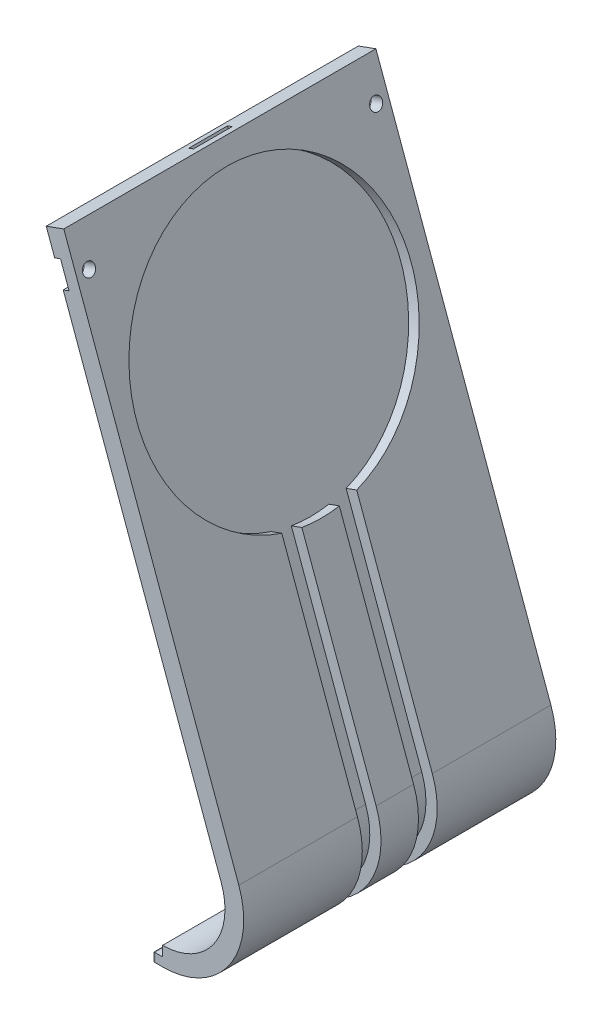
SolidWorks part; units mm, degrees
material "PLA"
ref_plane "前视基准面" through (0, 0, 0) normal (0, 0, 1) x (1, 0, 0)
ref_plane "上视基准面" through (0, 0, 0) normal (0, 1, 0) x (1, 0, 0)
ref_plane "右视基准面" through (0, 0, 0) normal (1, 0, 0) x (0, 0, -1)
other "Configuration Table"
sketch "草图2" plane through (0, 0, 0) normal (0, 0, 1) x (1, 0, 0)
  line L0 (38.2711, 18.4699) -> (5.8755, 107.4762) construction
  line L5 (38.2711, 18.4699) -> (10.2328, 95.5045)
  line L7 (38.2711, 18.4699) -> (8.6116, 99.9586) construction
  line L9 (9.2093, 101.2404) -> (11.5585, 102.0954) construction
  line L10 (28.8742, 5.0497) -> (28.8742, 4.0497) construction
  arc A0 (28.8742, 5.0497) -> (38.2711, 18.4699) centre (28.8742, 15.0497) ccw
  arc A1 (28.8742, 5.0497) -> (38.2711, 18.4699) centre (28.8742, 15.0497) ccw construction
  point P0 (9.5403, 97.4071)
  dimension "D2" = 10
  dimension "D1" = 5.74
extrude "整体拉伸-薄壁1" add sketch "草图2" along normal mid plane 50 thin
sketch "草图4" plane through (42.5494, 15.4867, 0) normal (0.9397, 0.342, 0) x (0, 0, -1)
  line L0 (-25, 86.245) -> (25, 86.245) construction
  circle A0 centre (0, 60.845) radius 22
  dimension "D1" = 44
  dimension "D2" = 25.4
extrude "中间圆切除-拉伸1" cut sketch "草图4" against normal blind 1.8
sketch "草图3" plane through (0, 0, 0) normal (0, 0, 1) x (1, 0, 0)
  line L0 (41.0902, 19.4959) -> (13.0519, 96.5306) construction
  line L1 (41.0902, 19.4959) -> (13.0519, 96.5306) construction
  line L2 (28.8742, 2.0497) -> (28.8742, 5.0497) construction
  line L5 (39.3988, 18.8803) -> (27.5722, 51.3735)
  line L6 (39.3988, 18.8803) -> (11.3604, 95.9149) construction
  line L7 (28.8742, 3.8497) -> (28.8742, 3.8497) construction
  line L9 (27.5722, 51.3735) -> (29.2636, 51.9891) construction
  line L16 (27.5722, 51.3735) -> (26.5461, 54.1926)
  line L17 (27.0769, 3.9492) -> (17.8463, 8.166) construction
  arc A0 (28.8742, 5.0497) -> (38.2711, 18.4699) centre (28.8742, 15.0497) ccw construction
  arc A1 (17.8463, 8.166) -> (41.0902, 19.4959) centre (28.8742, 15.0497) ccw construction
  arc A2 (28.8742, 3.8497) -> (39.3988, 18.8803) centre (28.8742, 15.0497) ccw
  dimension "D2" = 3
  dimension "D1" = 1.8
extrude "线槽切除-拉伸-薄壁1" cut sketch "草图3" against normal blind 3 from offset 6 thin
mirror "镜向1" about plane through (0, 0, 0) normal (0, 0, 1) of "线槽切除-拉伸-薄壁1"
sketch "草图11" plane through (28.8742, 0, 0) normal (-1, 0, 0) x (0, 0, 1)
  line L0 (-25, 2.0497) -> (-25, 5.0497) construction
  line L1 (-25, 3.4497) -> (-6.1, 3.4497)
  line L2 (-25, 3.4497) -> (-25, 2.0497)
  line L3 (-25, 2.0497) -> (-6.1, 2.0497)
  line L4 (-6.1, 3.4497) -> (-6.1, 2.0497)
  line L5 (25, 2.0497) -> (6, 2.0497) construction
  line L6 (6.1, 3.4497) -> (25, 3.4497)
  line L7 (6.1, 3.4497) -> (6.1, 2.0497)
  line L8 (6.1, 2.0497) -> (25, 2.0497)
  line L9 (25, 3.4497) -> (25, 2.0497)
  line L11 (-6, 2.0497) -> (-6, 3.8497) construction
  line L13 (6, 2.0497) -> (6, 3.8497) construction
  line L14 (25, 5.0497) -> (-25, 5.0497) construction
  dimension "D1" = 1.6
  dimension "D2" = 0.1
  dimension "D3" = 0.1
  dimension "D4" = 1.6
extrude "底部卡扣凸台-拉伸3" add sketch "草图11" along normal blind 1.5
fillet "底部卡扣圆角1" radius 0.25 8 edges at (27.3742, 3.4497, 15.55) (27.3742, 2.7497, 25) (27.3742, 2.0497, 15.55) (27.3742, 2.7497, 6.1) (27.3742, 3.4497, -15.55) (27.3742, 2.7497, -6.1) (27.3742, 2.0497, -15.55) (27.3742, 2.7497, -25)
sketch "草图12" plane through (39.7304, 14.4607, 0) normal (-0.9397, -0.342, 0) x (0, 0, 1)
  line L0 (-36.5, 82.2828) -> (36.5, 82.2828) construction
  line L2 (-25, 4.2665) -> (-25, 86.245) construction
  line L3 (25, 4.2665) -> (25, 86.245) construction
  circle A0 centre (23, 80.2828) radius 1
  circle A1 centre (-23, 80.2828) radius 1
  dimension "D1" = 2
  dimension "D2" = 2
  dimension "D3" = 2
  dimension "D4" = 2
  dimension "D5" = 2
  dimension "D6" = 2
extrude "螺丝孔" cut sketch "草图12" against normal through all
sketch "草图13" plane through (39.7304, 14.4607, 0) normal (-0.9397, -0.342, 0) x (0, 0, 1)
  line L0 (25, 4.2665) -> (25, 86.245) construction
  line L1 (23, 82.2828) -> (25, 82.2828)
  line L3 (23, 78.2828) -> (25, 78.2828)
  line L4 (25, 82.2828) -> (25, 78.2828)
  line L5 (-36.5, 82.2828) -> (36.5, 82.2828) construction
  line L6 (0, 86.245) -> (0, 78.3622) construction
  line L7 (25, 86.245) -> (-25, 86.245) construction
  line L8 (-25, 82.2828) -> (-25, 78.2828)
  line L9 (-23, 78.2828) -> (-25, 78.2828)
  line L10 (-23, 82.2828) -> (-25, 82.2828)
  arc A0 (23, 82.2828) -> (23, 78.2828) centre (23, 80.2828) ccw
  arc A1 (-23, 82.2828) -> (-23, 78.2828) centre (-23, 80.2828) cw
  dimension "D1" = 4
extrude "切除-拉伸1" cut sketch "草图13" against normal blind 1
sketch "草图14" plane through (-29.4975, 81.0438, 0) normal (-0.342, 0.9397, 0) x (0.9397, 0.342, 0)
  line L0 (42.2802, -5.1) -> (45.2802, -5.1) construction
  line L1 (44.0802, 3.1) -> (43.2802, 3.1)
  line L2 (44.0802, 3.1) -> (44.0802, -3.1)
  line L3 (44.0802, -3.1) -> (43.2802, -3.1)
  line L4 (43.2802, 3.1) -> (43.2802, -3.1)
  line L5 (45.2802, 5.1) -> (42.2802, 5.1) construction
  line L6 (42.2802, -25) -> (42.2802, 25) construction
  line L7 (45.2802, -25) -> (45.2802, 25) construction
  dimension "D1" = 2
  dimension "D2" = 2
  dimension "D3" = 1
  dimension "D4" = 1.2
extrude "切除-拉伸2" cut sketch "草图14" against normal blind 1
